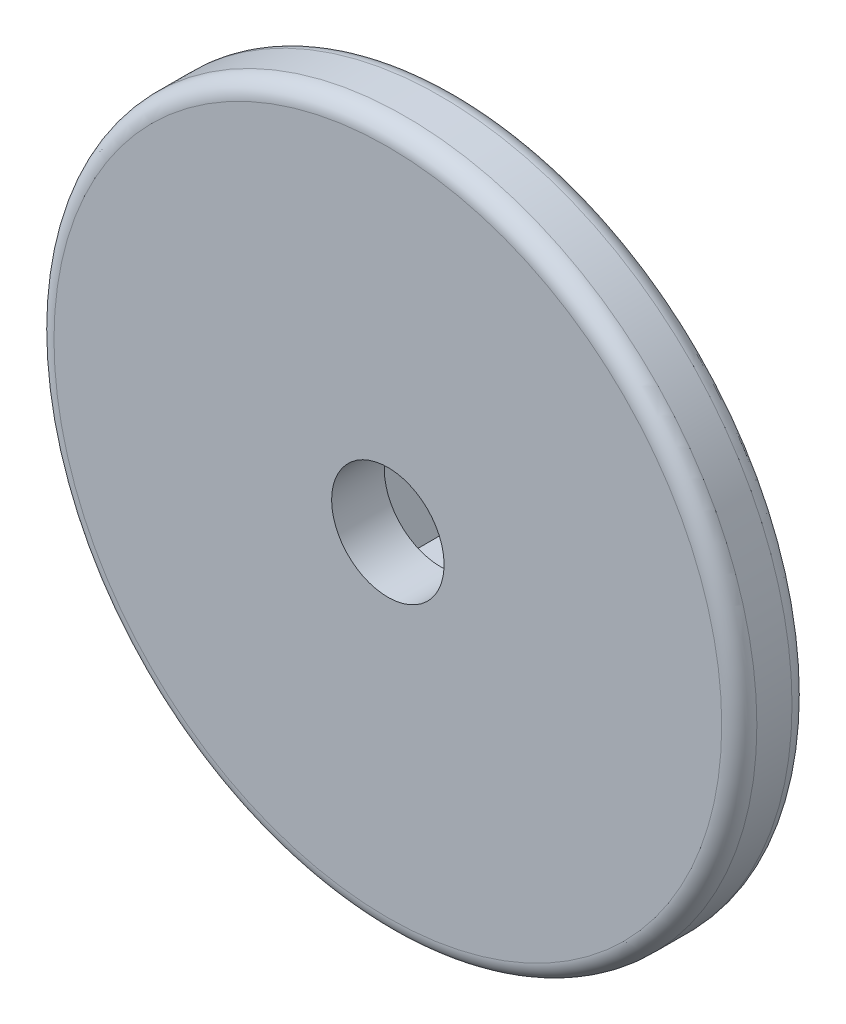
SolidWorks part; units mm, degrees
material "ABS"
ref_plane "Front Plane" through (0, 0, 0) normal (0, 0, 1) x (1, 0, 0)
ref_plane "Top Plane" through (0, 0, 0) normal (0, 1, 0) x (1, 0, 0)
ref_plane "Right Plane" through (0, 0, 0) normal (1, 0, 0) x (0, 0, -1)
sketch "Sketch1" plane through (0, 0, 0) normal (0, 1, 0) x (1, 0, 0)
  line L0 (0, 0) -> (9.5, 0)
  line L1 (10, 0.5) -> (10, 1.5)
  line L2 (9.5, 2) -> (7, 2)
  line L3 (7, 2) -> (6.193, 4)
  line L4 (6.193, 4) -> (4.693, 4)
  line L5 (4.693, 4) -> (4.0351, 3.5)
  line L6 (4.0351, 3.5) -> (0, 3.5)
  line L7 (0, 3.5) -> (0, 0)
  arc A0 (9.5, 0) -> (10, 0.5) centre (9.5, 0.5) ccw
  arc A1 (10, 1.5) -> (9.5, 2) centre (9.5, 1.5) ccw
  point P11 (10, 0)
  point P14 (10, 2)
  dimension "D7" = 0.5
  dimension "D1" = 10
  dimension "D2" = 2
  dimension "D3" = 4
  dimension "D4" = 3.5
  dimension "D5" = 1.5
  dimension "D6" = 3
revolve "Revolve1" add sketch "Sketch1" angle 360 about L7
sketch "Sketch2" plane through (0, 0, -3.5) normal (0, 0, -1) x (-1, 0, 0)
  circle A0 centre (0, 0) radius 1.6
  dimension "D1" = 3.2
extrude "Cut-Extrude1" cut sketch "Sketch2" against normal through all
sketch "Sketch3" plane through (0, 0, -3.5) normal (0, 0, -1) x (-1, 0, 0)
  line L1 (-1.3562, -2.8073) -> (1.7531, -2.5781)
  line L2 (1.7531, -2.5781) -> (3.1093, 0.2292)
  line L3 (3.1093, 0.2292) -> (1.3562, 2.8073)
  line L4 (1.3562, 2.8073) -> (-1.7531, 2.5781)
  line L5 (-1.7531, 2.5781) -> (-3.1093, -0.2292)
  line L6 (-3.1093, -0.2292) -> (-1.3562, -2.8073)
  circle A0 centre (0, 0) radius 2.7 construction
  dimension "D1" = 5.4
extrude "Cut-Extrude2" cut sketch "Sketch3" against normal blind 2
